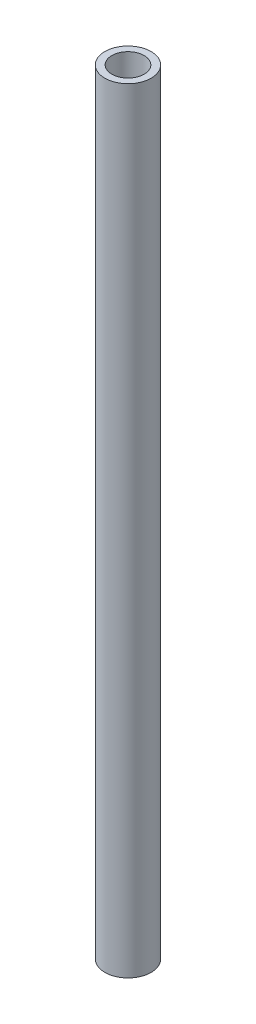
SolidWorks part; units mm, degrees
ref_plane "Front Plane" through (0, 0, 0) normal (0, 0, 1) x (1, 0, 0)
ref_plane "Top Plane" through (0, 0, 0) normal (0, 1, 0) x (1, 0, 0)
ref_plane "Right Plane" through (0, 0, 0) normal (1, 0, 0) x (0, 0, -1)
sketch "Sketch1" plane through (0, 0, 0) normal (0, 0, 1) x (1, 0, 0)
  line L0 (148.2962, 376.6083) -> (148.2962, 41.6083)
  line L1 (138.2962, 709.4745) -> (138.2962, 41.6083) construction
  dimension "D1" = 335
  dimension "D2" = 10
revolve "Revolve-Thin1" add sketch "Sketch1" angle 360 about L1
